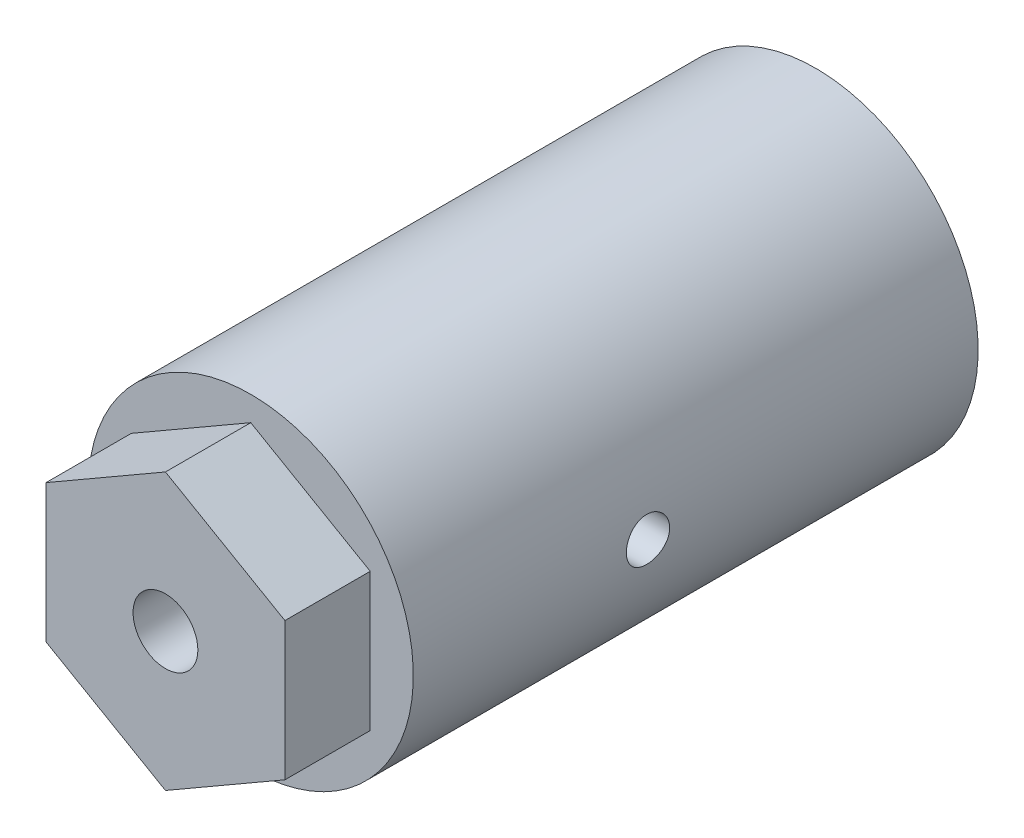
SolidWorks part; units mm, degrees
material "6061-T6 (SS)"
ref_plane "Front Plane" through (0, 0, 0) normal (0, 0, 1) x (1, 0, 0)
ref_plane "Top Plane" through (0, 0, 0) normal (0, 1, 0) x (1, 0, 0)
ref_plane "Right Plane" through (0, 0, 0) normal (1, 0, 0) x (0, 0, -1)
sketch "Sketch1" plane through (0, 0, 0) normal (0, 0, 1) x (1, 0, 0)
  line L1 (0, 8.0829) -> (-7, 4.0415)
  line L2 (-7, 4.0415) -> (-7, -4.0415)
  line L3 (-7, -4.0415) -> (0, -8.0829)
  line L4 (0, -8.0829) -> (7, -4.0415)
  line L5 (7, -4.0415) -> (7, 4.0415)
  line L6 (7, 4.0415) -> (0, 8.0829)
  circle A1 centre (0, 0) radius 7 construction
extrude "Boss-Extrude2" add sketch "Sketch1" along normal blind 5
sketch "Sketch2" plane through (0, 0, 0) normal (0, 0, -1) x (-1, 0, 0)
  circle A0 centre (0, 0) radius 9.525
  dimension "D1" = 19.05
extrude "Boss-Extrude3" add sketch "Sketch2" along normal blind 33.1
sketch "Sketch3" plane through (0, 0, -33.1) normal (0, 0, -1) x (-1, 0, 0)
  circle A0 centre (0, 0) radius 3.9688
  dimension "D1" = 7.9375
extrude "Cut-Extrude1" cut sketch "Sketch3" against normal blind 19.05
sketch "Sketch4" plane through (0, 0, 5) normal (0, 0, 1) x (1, 0, 0)
  circle A0 centre (0, 0) radius 1.27
  dimension "D1" = 2.54
extrude "Cut-Extrude2" cut sketch "Sketch4" against normal blind 19.05
hole_wizard "#10-24 Tapped Hole1" positions "3DSketch1" profile "Sketch5" tap size "#10-24" standard "Ansi Inch"
sketch3d "3DSketch1"
  line L0 (0, 0, -14.05) -> (0, 0, 5) construction
  point P0 (0, 0, 5)
sketch "Sketch5" plane through (0, 0, 5) normal (1, 0, 0) x (0, -1, 0)
  line L0 (0, 0) -> (0, 16.0908)
  line L1 (0, 16.0908) -> (1.8986, 14.95)
  line L2 (1.8986, 14.95) -> (1.8986, 0)
  line L5 (1.8986, 0) -> (0, 0)
  line L10 (0, 16.0908) -> (-1.8987, 14.95) construction
  line L11 (0, -6.35) -> (0, 107.95) construction
  dimension "Tap Drill Dia." = 3.7973
  dimension "Tap Drill Depth" = 14.95
  dimension "Drill Angle" = 118
cosmetic thread "Hole Thread1" parameters "D1"=9.65, "D2"=4.826
ref_plane "Plane1" through (9.525, 0, 0) normal (1, 0, 0) x (0, 0, -1)
sketch "Sketch6" plane through (9.525, 0, 0) normal (1, 0, 0) x (0, 0, -1)
  circle A0 centre (13.7551, 0) radius 1.27
  dimension "D1" = 2.54
extrude "Cut-Extrude3" cut sketch "Sketch6" against normal blind 8
